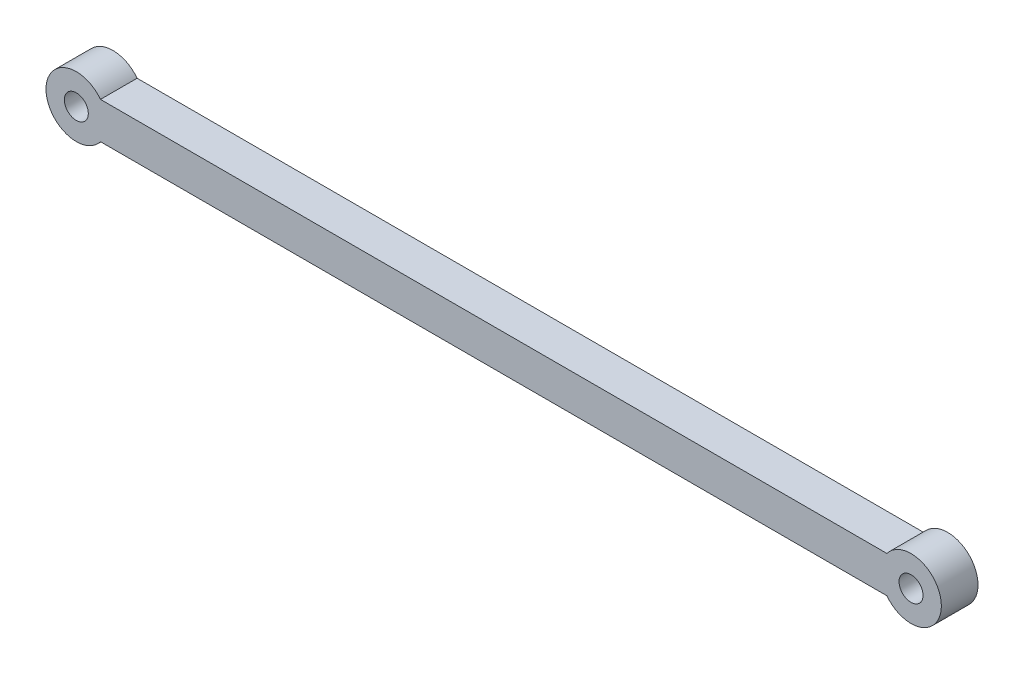
SolidWorks part; units mm, degrees
ref_plane "Front Plane" through (0, 0, 0) normal (0, 0, 1) x (1, 0, 0)
ref_plane "Top Plane" through (0, 0, 0) normal (0, 1, 0) x (1, 0, 0)
ref_plane "Right Plane" through (0, 0, 0) normal (1, 0, 0) x (0, 0, -1)
sketch "Sketch3" plane through (0, 0, 0) normal (0, 0, 1) x (1, 0, 0)
  line L0 (-625.3521, 0) -> (-125.3521, 0) construction
  line L2 (-610.8885, 10.9763) -> (-139.8157, 10.9763)
  line L3 (-610.8885, 10.9763) -> (-610.8885, -10.9763)
  line L4 (-610.8885, -10.9763) -> (-139.8157, -10.9763)
  line L5 (-139.8157, 10.9763) -> (-139.8157, -10.9763)
  circle A0 centre (-625.3521, 0) radius 18.1569
  circle A1 centre (-125.3521, 0) radius 18.1569
  point P9 (0, 0)
  point P10 (0, 0)
  dimension "D2" = 36.3139
  dimension "D1" = 500
  dimension "D3" = 21.9525
extrude "Boss-Extrude1" add sketch "Sketch3" along normal mid plane 21.9525 contours L2 L5 L4 L3 | A0 | A1
sketch "Sketch4" plane through (0, 0, 10.9763) normal (0, 0, 1) x (1, 0, 0)
  circle A0 centre (-625.3521, 0) radius 7.1807
  circle A1 centre (-125.3521, 0) radius 7.1807
  dimension "D1" = 14.3614
extrude "Cut-Extrude1" cut sketch "Sketch4" against normal through all
